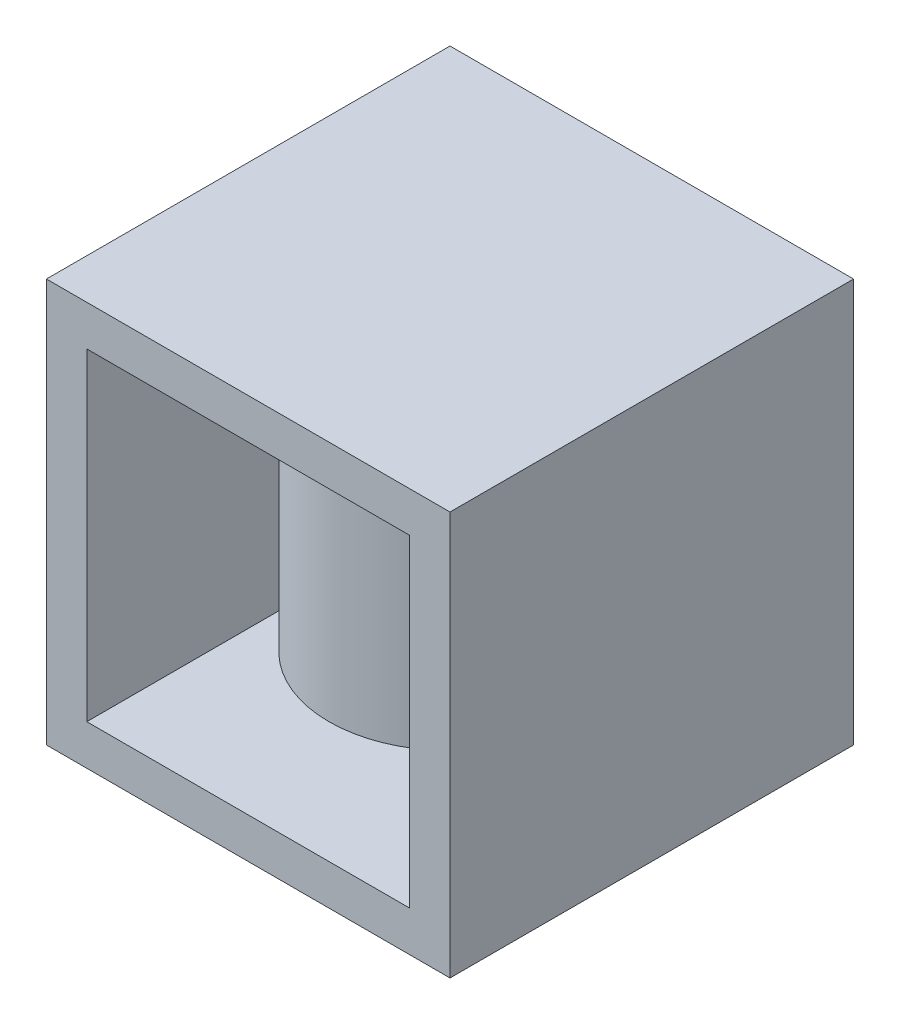
SolidWorks part; units mm, degrees
ref_plane "Front Plane" through (0, 0, 0) normal (0, 0, 1) x (1, 0, 0)
ref_plane "Top Plane" through (0, 0, 0) normal (0, 1, 0) x (1, 0, 0)
ref_plane "Right Plane" through (0, 0, 0) normal (1, 0, 0) x (0, 0, -1)
sketch "Sketch1" plane through (0, 0, 0) normal (0, 0, 1) x (1, 0, 0)
  line L1 (0, 0) -> (1000, 0)
  line L2 (0, 0) -> (0, 1000)
  line L3 (0, 1000) -> (1000, 1000)
  line L4 (1000, 0) -> (1000, 1000)
  line L5 (100, 900) -> (900, 900)
  line L6 (100, 900) -> (100, 100)
  line L7 (100, 100) -> (900, 100)
  line L8 (900, 900) -> (900, 100)
  dimension "D1" = 1000
  dimension "D2" = 1000
  dimension "D3" = 100
  dimension "D4" = 100
  dimension "D5" = 100
  dimension "D6" = 100
extrude "Boss-Extrude1" add sketch "Sketch1" along normal blind 1000 contours L1 L4 L3 L2 L5 L8 L7 L6
sketch "Sketch2" plane through (0, 900, 0) normal (0, -1, 0) x (1, 0, 0)
  line L0 (0, 1000) -> (0, 0) construction
  line L4 (0, 0) -> (1000, 0) construction
  circle A0 centre (500, 500) radius 300
  dimension "D1" = 600
  dimension "D2" = 500
  dimension "D3" = 500
extrude "Boss-Extrude2" add sketch "Sketch2" along normal blind 700
